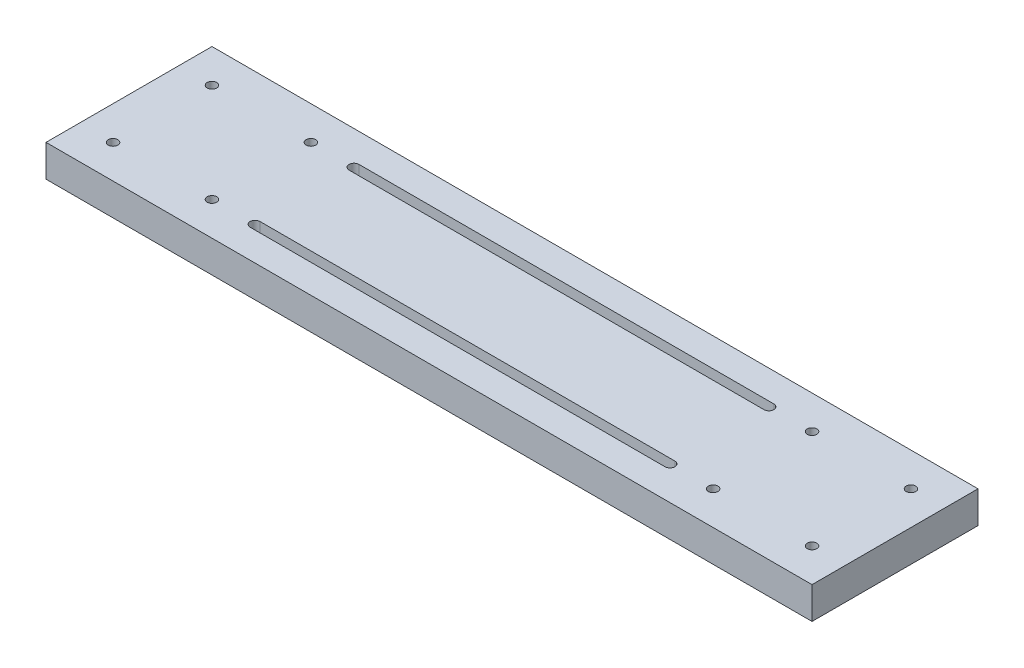
SolidWorks part; units mm, degrees
other "标注1"
sketch "草图14" plane through (120, 10, 26) normal (0.4262, 0.9045, 0.0144) x (0.9046, -0.4259, -0.0186)
other "细节项目1"
other "细节项目2"
other "标注2"
sketch "草图15" plane through (-120, 0, -26) normal (-0.102, -0.9853, -0.1367) x (-0.9938, 0.1069, -0.0292)
other "标注3"
sketch "草图16" plane through (-120, 0, -26) normal (-0.3573, -0.9333, -0.0352) x (-0.934, 0.3573, 0.0071)
other "标注4"
sketch "草图17" plane through (120, 10, -26) normal (0.5146, 0.8563, -0.0433) x (0.8572, -0.5127, 0.048)
other "细节项目3"
other "细节项目4"
ref_plane "前视基准面" through (0, 0, 0) normal (0, 0, 1) x (1, 0, 0)
ref_plane "上视基准面" through (0, 0, 0) normal (0, 1, 0) x (1, 0, 0)
ref_plane "右视基准面" through (0, 0, 0) normal (1, 0, 0) x (0, 0, -1)
sketch "草图11" plane through (0, 0, 0) normal (0, 1, 0) x (1, 0, 0)
  line L0 (-65, 15.5) -> (65, 15.5) construction
  line L1 (-120, 26) -> (120, 26)
  line L2 (-120, 26) -> (-120, -26)
  line L3 (-120, -26) -> (120, -26)
  line L4 (120, 26) -> (120, -26)
  line L5 (-120, 26) -> (120, -26) construction
  line L6 (-120, -26) -> (120, 26) construction
  line L7 (-65, 21) -> (-23, 21)
  line L8 (-65, 21) -> (-65, -21)
  line L9 (-65, -21) -> (-23, -21)
  line L10 (-23, 21) -> (-23, -21)
  line L11 (-65, 21) -> (-23, -21) construction
  line L12 (-65, -21) -> (-23, 21) construction
  line L13 (3, 21) -> (45, 21)
  line L14 (3, 21) -> (3, -21)
  line L15 (3, -21) -> (45, -21)
  line L16 (45, 21) -> (45, -21)
  line L17 (3, 21) -> (45, -21) construction
  line L18 (3, -21) -> (45, 21) construction
  line L19 (73, 21) -> (115, 21)
  line L20 (73, 21) -> (73, -21)
  line L21 (73, -21) -> (115, -21)
  line L22 (115, 21) -> (115, -21)
  line L23 (73, 21) -> (115, -21) construction
  line L24 (73, -21) -> (115, 21) construction
  line L25 (-115, 21) -> (-73, 21)
  line L26 (-115, 21) -> (-115, -21)
  line L27 (-115, -21) -> (-73, -21)
  line L28 (-73, 21) -> (-73, -21)
  line L29 (-115, 21) -> (-73, -21) construction
  line L30 (-115, -21) -> (-73, 21) construction
  line L31 (-45, 21) -> (-3, 21)
  line L32 (-45, 21) -> (-45, -21)
  line L33 (-45, -21) -> (-3, -21)
  line L34 (-3, 21) -> (-3, -21)
  line L35 (-45, 21) -> (-3, -21) construction
  line L36 (-45, -21) -> (-3, 21) construction
  line L37 (23, 21) -> (65, 21)
  line L38 (23, 21) -> (23, -21)
  line L39 (23, -21) -> (65, -21)
  line L40 (65, 21) -> (65, -21)
  line L41 (23, 21) -> (65, -21) construction
  line L42 (23, -21) -> (65, 21) construction
  line L43 (-65, 17.05) -> (65, 17.05)
  line L44 (-65, 13.95) -> (65, 13.95)
  line L45 (-65, -15.5) -> (65, -15.5) construction
  line L46 (-65, -13.95) -> (65, -13.95)
  line L47 (-65, -17.05) -> (65, -17.05)
  circle A1 centre (-109.5, 15.5) radius 1.5
  circle A2 centre (-78.5, 15.5) radius 1.5
  circle A3 centre (-109.5, -15.5) radius 1.5
  circle A4 centre (-78.5, -15.5) radius 1.5
  circle A8 centre (78.5, 15.5) radius 1.5
  circle A9 centre (109.5, 15.5) radius 1.5
  circle A10 centre (109.5, -15.5) radius 1.5
  circle A12 centre (78.5, -15.5) radius 1.5
  arc A13 (-65, 17.05) -> (-65, 13.95) centre (-65, 15.5) ccw
  arc A14 (65, 13.95) -> (65, 17.05) centre (65, 15.5) ccw
  arc A15 (-65, -13.95) -> (-65, -17.05) centre (-65, -15.5) ccw
  arc A16 (65, -17.05) -> (65, -13.95) centre (65, -15.5) ccw
  point P0 (0, 0)
  point P6 (-44, 0)
  point P11 (24, 0)
  point P16 (94, 0)
  point P21 (-94, 0)
  point P26 (-24, 0)
  point P31 (44, 0)
  point P52 (0, 15.5)
  point P61 (0, -15.5)
  point P66 (0, 0)
  point P67 (0, 0)
  point P68 (0, 0)
  point P69 (0, 0)
  dimension "D10" = 31
  dimension "D11" = 3
  dimension "D12" = 1.55
  dimension "D13" = 1.55
  dimension "D1" = 5
  dimension "D2" = 5
  dimension "D3" = 50
  dimension "D4" = 5
  dimension "D5" = 42
  dimension "D6" = 50
  dimension "D7" = 70
  dimension "D8" = 70
  dimension "D9" = 6
sketch "草图12" plane through (0, 0, 0) normal (0, 1, 0) x (1, 0, 0)
  line L1 (-120, 26) -> (120, 26)
  line L2 (-120, 26) -> (-120, -26)
  line L3 (-120, -26) -> (120, -26)
  line L4 (120, 26) -> (120, -26)
extrude "凸台-拉伸1" add sketch "草图12" along normal blind 10
extrude "切除-拉伸4" cut sketch "草图11" along normal up to next contours A9 | A10 | A8 | A12 | L44 A14 L43 A13 | L46 A16 L47 A15 | A2 | A4 | A3 | A1
